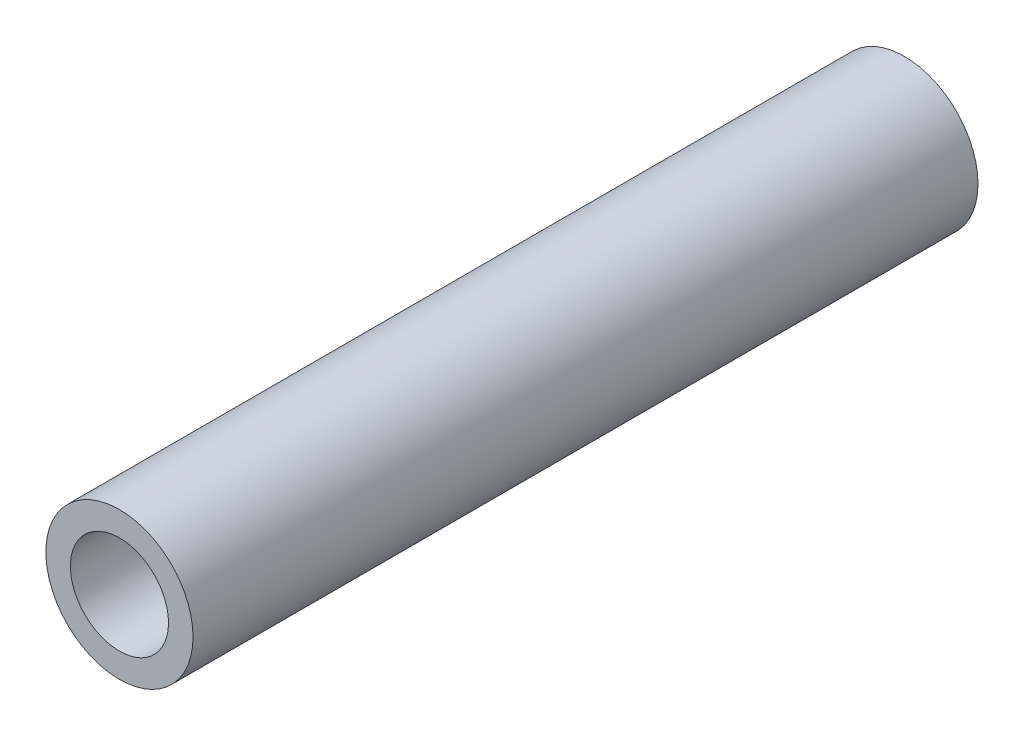
SolidWorks part; units mm, degrees
ref_plane "前视基准面" through (0, 0, 0) normal (0, 0, 1) x (1, 0, 0)
ref_plane "上视基准面" through (0, 0, 0) normal (0, 1, 0) x (1, 0, 0)
ref_plane "右视基准面" through (0, 0, 0) normal (1, 0, 0) x (0, 0, -1)
sketch "草图1" plane through (0, 0, 0) normal (0, 0, 1) x (1, 0, 0)
  circle A0 centre (0, 0) radius 1.5
extrude "凸台-拉伸1" add sketch "草图1" along normal blind 16
sketch "草图2" plane through (0, 0, 16) normal (0, 0, 1) x (1, 0, 0)
  circle A0 centre (0, 0) radius 1
extrude "切除-拉伸1" cut sketch "草图2" against normal blind 16
